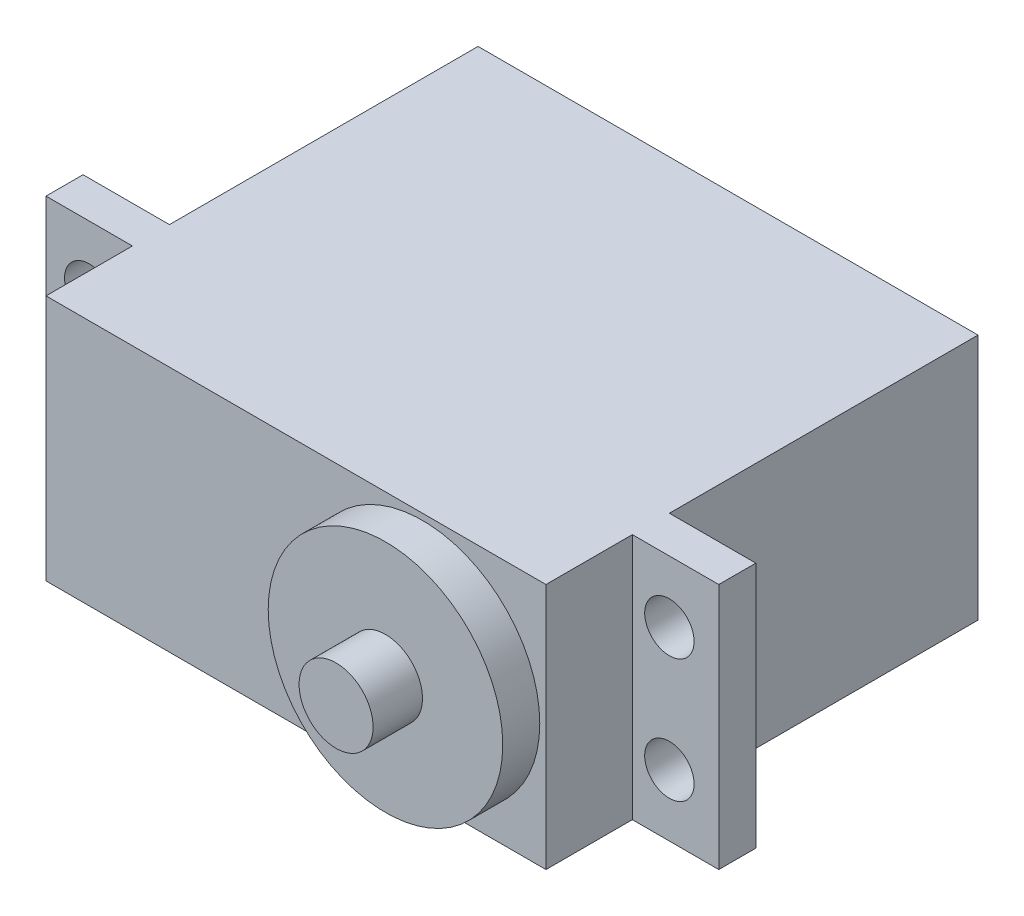
SolidWorks part; units mm, degrees
ref_plane "前视基准面" through (0, 0, 0) normal (0, 0, 1) x (1, 0, 0)
ref_plane "上视基准面" through (0, 0, 0) normal (0, 1, 0) x (1, 0, 0)
ref_plane "右视基准面" through (0, 0, 0) normal (1, 0, 0) x (0, 0, -1)
other "Configuration Table"
sketch "草图1" plane through (0, 0, 0) normal (0, 0, 1) x (1, 0, 0)
  line L1 (-30.5, -10) -> (10, -10)
  line L2 (-30.5, -10) -> (-30.5, 10)
  line L3 (-30.5, 10) -> (10, 10)
  line L4 (10, -10) -> (10, 10)
extrude "MG995_case_photo_approx35" add sketch "草图1" along normal blind 35
sketch "草图2" plane through (0, 0, 0) normal (0, 0, 1) x (1, 0, 0)
  line L1 (-37.5, -10) -> (17, -10)
  line L2 (-37.5, -10) -> (-37.5, 10)
  line L3 (-37.5, 10) -> (17, 10)
  line L4 (17, -10) -> (17, 10)
extrude "Mounting_ears_APPROX54p5" add sketch "草图2" along normal blind 3 from offset 25
sketch "草图3" plane through (0, 0, 0) normal (0, 0, 1) x (1, 0, 0)
  circle A0 centre (0, 0) radius 9.5
extrude "Raised_cover_APPROX" add sketch "草图3" along normal blind 38
sketch "草图4" plane through (0, 0, 0) normal (0, 0, 1) x (1, 0, 0)
  circle A0 centre (0, 0) radius 3
extrude "Output_shaft_envelope_NO_SPLINE" add sketch "草图4" along normal blind 42
sketch "草图5" plane through (0, 0, 0) normal (0, 0, 1) x (1, 0, 0)
  circle A0 centre (-34, -5) radius 2
  circle A1 centre (-34, 5) radius 2
  circle A2 centre (13, -5) radius 2
  circle A3 centre (13, 5) radius 2
extrude "Ear_holes_REFERENCE_47x10" cut sketch "草图5" against normal through all and the other way through all
